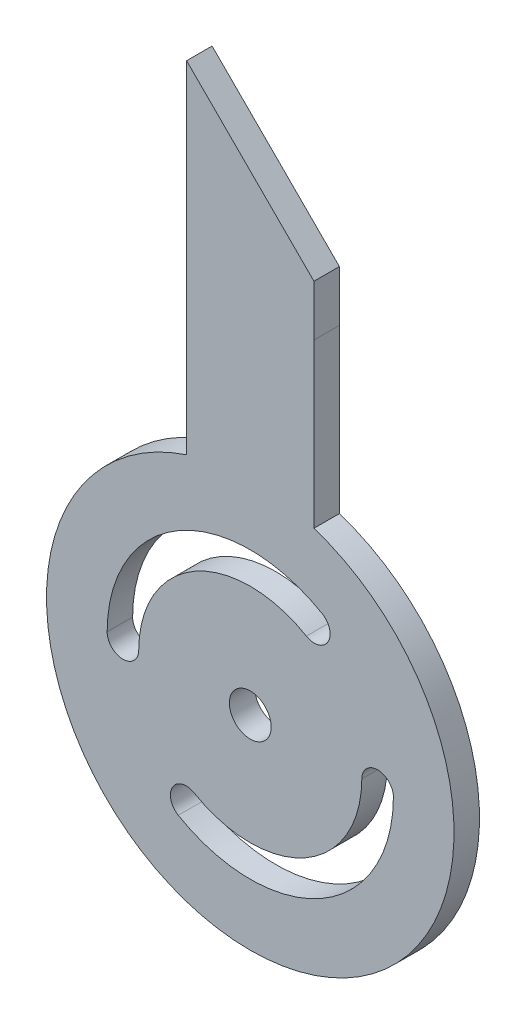
SolidWorks part; units mm, degrees
ref_plane "前视基准面" through (0, 0, 0) normal (0, 0, 1) x (1, 0, 0)
ref_plane "上视基准面" through (0, 0, 0) normal (0, 1, 0) x (1, 0, 0)
ref_plane "右视基准面" through (0, 0, 0) normal (1, 0, 0) x (0, 0, -1)
sketch "草图2" plane through (0, 0, 0) normal (0, 0, 1) x (1, 0, 0)
  line L1 (-12.5, 70) -> (12.5, 70)
  line L2 (-12.5, 70) -> (-12.5, 37.9967)
  line L4 (12.5, 70) -> (12.5, 37.9967)
  arc A0 (-12.5, 37.9967) -> (12.5, 37.9967) centre (0, 0) ccw
  dimension "D1" = 80
  dimension "D2" = 25
  dimension "D3" = 70
extrude "凸台-拉伸1" add sketch "草图2" along normal blind 5
ref_plane "基准面1" through (0, 0, 5) normal (0, 0, 1) x (1, 0, 0)
sketch "草图3" plane through (0, 0, 5) normal (0, 0, 1) x (1, 0, 0)
  line L1 (-12.5, 70) -> (12.5049, 70)
  line L2 (-12.5, 70) -> (-12.5, 95)
  line L3 (-12.5, 95) -> (12.5049, 95)
  line L4 (12.5049, 70) -> (12.5049, 95)
  dimension "D1" = 25
extrude "凸台-拉伸2" add sketch "草图3" against normal blind 5
sketch "草图4" plane through (0, 0, 5) normal (0, 0, 1) x (1, 0, 0)
  line L0 (12.5024, 70) -> (12.5049, 95) construction
  line L1 (-12.5, 95) -> (12.5024, 95)
  line L2 (-12.5, 95) -> (12.5024, 70)
  line L4 (12.5024, 95) -> (12.5024, 70)
  dimension "D2" = 25.0024
extrude "切除-拉伸2" cut sketch "草图4" against normal blind 5
sketch "草图5" plane through (0, 0, 0) normal (0, 0, -1) x (-1, 0, 0)
  circle A0 centre (0, 0) radius 4.1
  dimension "D1" = 8.2
extrude "切除-拉伸3" cut sketch "草图5" against normal blind 5
sketch "草图7" plane through (0, 0, 0) normal (0, 0, -1) x (-1, 0, 0)
  arc A0 (24.9999, 0.0857) -> (-12.5742, 21.6076) centre (0, 0) ccw construction
  arc A1 (28.0998, 0.0963) -> (-14.1334, 24.287) centre (0, 0) ccw
  arc A2 (21.8999, 0.0751) -> (-11.015, 18.9283) centre (0, 0) ccw
  arc A3 (21.8999, 0.0751) -> (28.0998, 0.0963) centre (24.9999, 0.0857) ccw
  arc A4 (-14.1334, 24.287) -> (-11.015, 18.9283) centre (-12.5742, 21.6076) ccw
  circle A5 centre (0, 0) radius 4.1 construction
  arc A6 (-25.0004, 0.0857) -> (12.5736, -21.4362) centre (-0.0006, 0.1714) ccw construction
  arc A7 (-28.1004, 0.0751) -> (14.1328, -24.1156) centre (-0.0006, 0.1714) ccw
  arc A8 (-21.9005, 0.0963) -> (11.0144, -18.7569) centre (-0.0006, 0.1714) ccw
  arc A9 (-21.9005, 0.0963) -> (-28.1004, 0.0751) centre (-25.0004, 0.0857) ccw
  arc A10 (14.1328, -24.1156) -> (11.0144, -18.7569) centre (12.5736, -21.4362) ccw
  point P4 (12.4257, 21.6934)
  point P16 (-12.4263, -21.5219)
  point P21 (-0.0003, 0.0857)
  dimension "D1" = 20.9
  dimension "D2" = 2
extrude "切除-拉伸4" cut sketch "草图7" against normal blind 5
sketch "草图8" plane through (0, 0, 0) normal (0, 0, -1) x (-1, 0, 0)
  line L1 (-12.5024, 70) -> (12.4976, 70)
  line L2 (-12.5024, 70) -> (-12.5024, 105)
  line L3 (-12.5024, 105) -> (12.4976, 105)
  line L4 (12.4976, 70) -> (12.4976, 105)
  dimension "D1" = 25
  dimension "D2" = 35
extrude "凸台-拉伸3" add sketch "草图8" against normal blind 5
sketch "草图9" plane through (0, 0, 0) normal (0, 0, -1) x (-1, 0, 0)
  line L1 (-12.5024, 105) -> (12.5, 105)
  line L2 (-12.5024, 105) -> (-12.5024, 80)
  line L5 (-12.5024, 80) -> (12.5, 105)
  dimension "D1" = 25
extrude "切除-拉伸5" cut sketch "草图9" against normal blind 5
